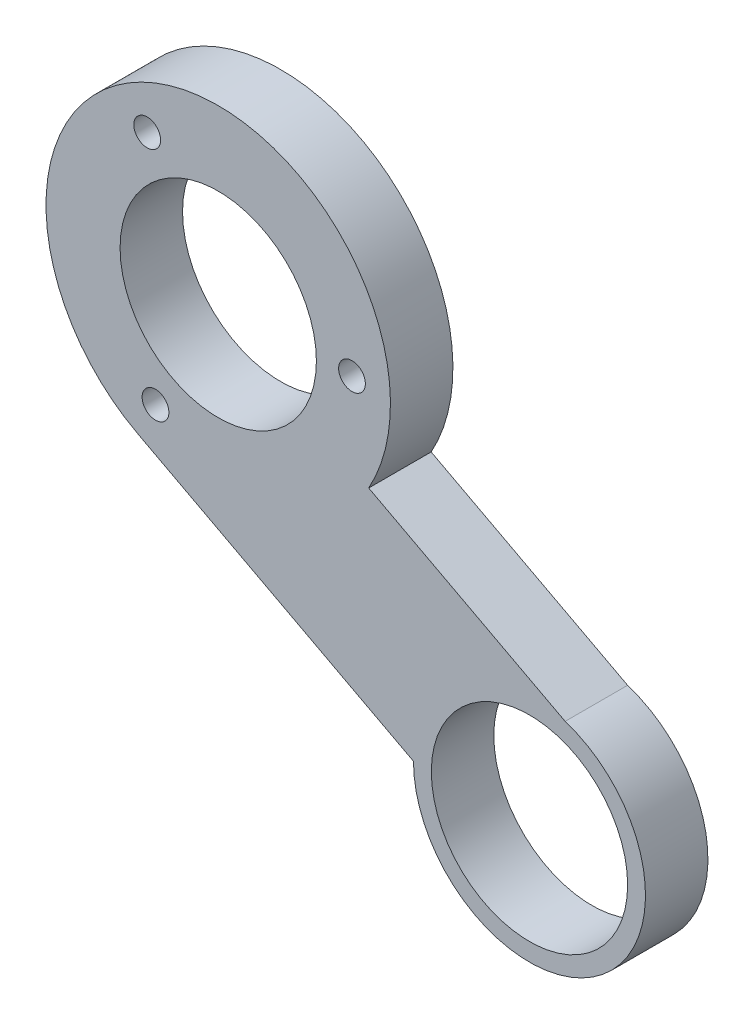
SolidWorks part; units mm, degrees
ref_plane "Front Plane" through (0, 0, 0) normal (0, 0, 1) x (1, 0, 0)
ref_plane "Top Plane" through (0, 0, 0) normal (0, 1, 0) x (1, 0, 0)
ref_plane "Right Plane" through (0, 0, 0) normal (1, 0, 0) x (0, 0, -1)
sketch "Sketch1" plane through (0, 0, 0) normal (0, 0, 1) x (1, 0, 0)
  line L0 (2.7345, -4.0104) -> (24.7494, -15.6495)
  line L1 (-23.1481, -11.6829) -> (7.7527, -28.0199)
  circle A0 centre (-14.1274, 5.3793) radius 19.3
  circle A1 centre (-14.1274, 5.3793) radius 11
  circle A2 centre (-22.0878, 18.0927) radius 1.5
  circle A3 centre (0.863, 5.9165) radius 1.5
  circle A4 centre (-21.1574, -7.8714) radius 1.5
  circle A5 centre (20.7527, -28.0199) radius 11
  circle A6 centre (20.7527, -28.0199) radius 13
  dimension "D1" = 22
  dimension "D2" = 38.6
  dimension "D3" = 22
  dimension "D4" = 26
extrude "Boss-Extrude1" add sketch "Sketch1" along normal up to surface (7 mm away) contours A6 L0 A0 L1 | A0 A4 A3 A2 A1 | L0 A6 A5
